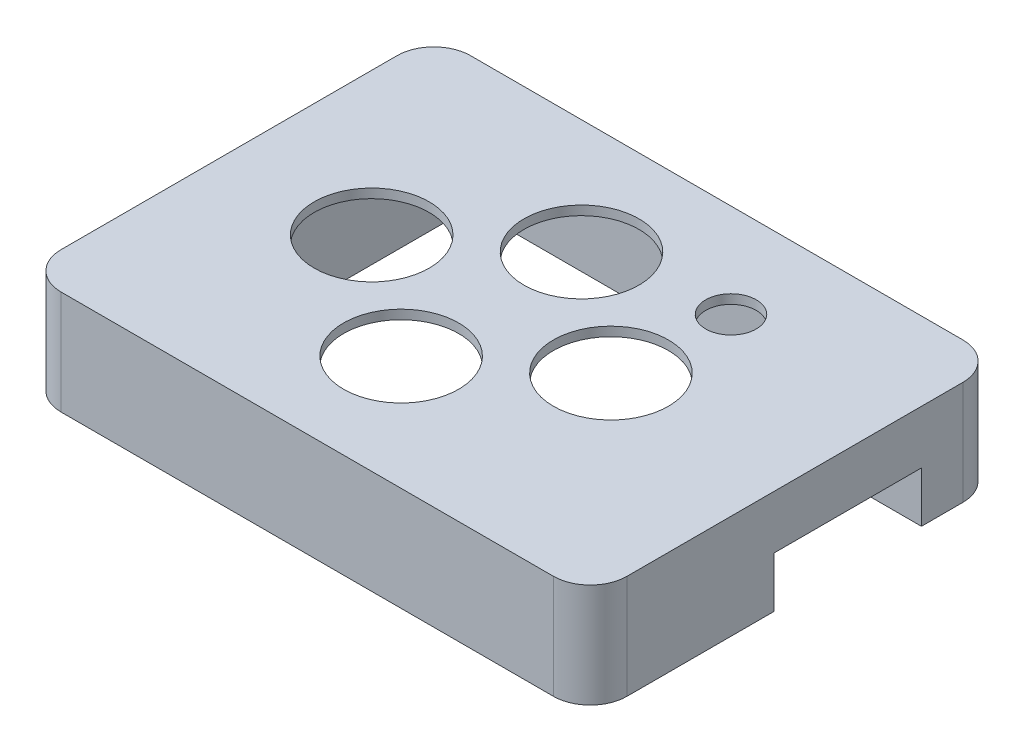
SolidWorks part; units mm, degrees
ref_plane "Front Plane" through (0, 0, 0) normal (0, 0, 1) x (1, 0, 0)
ref_plane "Top Plane" through (0, 0, 0) normal (0, 1, 0) x (1, 0, 0)
ref_plane "Right Plane" through (0, 0, 0) normal (1, 0, 0) x (0, 0, -1)
sketch "Sketch1" plane through (0, 0, 0) normal (0, 1, 0) x (1, 0, 0)
  line L0 (-15.25, 0) -> (-2.25, 0) construction
  line L1 (23.75, -19.25) -> (-23.75, -19.25)
  line L2 (23.75, -19.25) -> (23.75, 19.25)
  line L3 (23.75, 19.25) -> (-23.75, 19.25)
  line L4 (-23.75, -19.25) -> (-23.75, 19.25)
  line L5 (23.75, -19.25) -> (-23.75, 19.25) construction
  line L6 (23.75, 19.25) -> (-23.75, -19.25) construction
  line L7 (-2.25, 0) -> (10.75, 0) construction
  line L8 (-2.25, 0) -> (-2.25, -9.8) construction
  line L9 (-2.25, 9.8) -> (-2.25, 0) construction
  circle A0 centre (-2.25, 9.8) radius 6.25
  circle A1 centre (10.75, 0) radius 6.25
  circle A2 centre (-15.25, 0) radius 6.25
  circle A3 centre (-2.25, -9.8) radius 6.25
  circle A4 centre (11.75, 12.05) radius 2.75
  point P0 (0, 0)
  dimension "D1" = 12.5
  dimension "D4" = 9.45
  dimension "D5" = 26
  dimension "D6" = 19.25
  dimension "D7" = 5.5
  dimension "D9" = 12
  dimension "D10" = 7.2
  dimension "D2" = 38.5
  dimension "D3" = 47.5
  dimension "D8" = 13
extrude "Boss-Extrude2" add sketch "Sketch1" along normal blind 1
sketch "Sketch2" plane through (0, 1, 0) normal (0, 1, 0) x (1, 0, 0)
  line L0 (0, 0) -> (0, 22.25) construction
  line L1 (30.75, -22.25) -> (-30.75, -22.25)
  line L2 (30.75, -22.25) -> (30.75, 22.25)
  line L3 (30.75, 22.25) -> (-30.75, 22.25)
  line L4 (-30.75, -22.25) -> (-30.75, 22.25)
  line L5 (30.75, -22.25) -> (-30.75, 22.25) construction
  line L6 (30.75, 22.25) -> (-30.75, -22.25) construction
  line L7 (23.75, -19.25) -> (-23.75, -19.25)
  line L8 (23.75, -19.25) -> (23.75, 19.25)
  line L9 (23.75, 19.25) -> (-23.75, 19.25)
  line L10 (-23.75, -19.25) -> (-23.75, 19.25)
  line L11 (23.75, -19.25) -> (-23.75, 19.25) construction
  line L12 (23.75, 19.25) -> (-23.75, -19.25) construction
  line L14 (-30.75, 0) -> (0, 0) construction
  circle A0 centre (-27.25, 18.75) radius 1.55
  circle A1 centre (-27.25, 18.75) radius 3.5 construction
  circle A2 centre (27.25, 18.75) radius 1.55
  circle A3 centre (27.25, -18.75) radius 1.55
  circle A4 centre (-27.25, -18.75) radius 1.55
  point P0 (0, 0)
  point P6 (0, 0)
  dimension "D3" = 3.1
  dimension "D1" = 3
  dimension "D2" = 7
extrude "Boss-Extrude3" add sketch "Sketch2" against normal blind 11.3
sketch "Sketch3" plane through (0, 1, 0) normal (0, -1, 0) x (1, 0, 0)
  circle A0 centre (27.25, -18.75) radius 1.55 construction
  circle A1 centre (27.25, 18.75) radius 1.55 construction
  circle A2 centre (-27.25, 18.75) radius 1.55 construction
  circle A3 centre (-27.25, -18.75) radius 1.55 construction
  circle A4 centre (27.25, -18.75) radius 1.55
  circle A5 centre (27.25, 18.75) radius 1.55
  circle A6 centre (-27.25, 18.75) radius 1.55
  circle A7 centre (-27.25, -18.75) radius 1.55
extrude "Boss-Extrude4" add sketch "Sketch3" along normal blind 2
fillet "Fillet2" radius 4 4 edges at (-30.75, -4.65, 22.25) (-30.75, -4.65, -22.25) (30.75, -4.65, -22.25) (30.75, -4.65, 22.25)
sketch "Sketch4" plane through (23.75, 0, 0) normal (-1, 0, 0) x (0, 0, 1)
  line L0 (-18.25, -10.3) -> (18.25, -10.3) construction
  line L1 (2.25, -10.3) -> (-13.75, -10.3)
  line L2 (2.25, -10.3) -> (2.25, -4.8)
  line L3 (2.25, -4.8) -> (-13.75, -4.8)
  line L4 (-13.75, -10.3) -> (-13.75, -4.8)
  line L5 (-22.25, 1) -> (-22.25, -10.3) construction
  point P8 (0, 0)
  point P9 (2.25, -5.0267)
  point P11 (4.0329, -15.8571)
  point P12 (2.8589, -16.5664)
  dimension "D1" = 8.5
  dimension "D2" = 16
  dimension "D3" = 5.5
extrude "Cut-Extrude1" cut sketch "Sketch4" against normal blind 8
